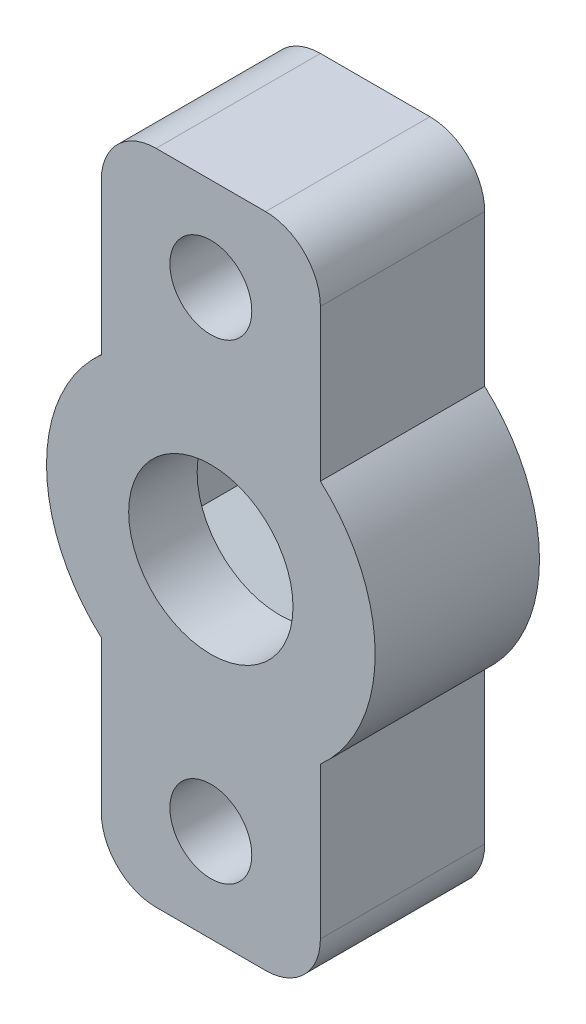
SolidWorks part; units mm, degrees
ref_plane "前视基准面" through (0, 0, 0) normal (0, 0, 1) x (1, 0, 0)
ref_plane "上视基准面" through (0, 0, 0) normal (0, 1, 0) x (1, 0, 0)
ref_plane "右视基准面" through (0, 0, 0) normal (1, 0, 0) x (0, 0, -1)
sketch "草图1" plane through (0, 0, 0) normal (0, 0, 1) x (1, 0, 0)
  line L0 (-5.08, 12.7) -> (-5.08, 5.6796)
  line L1 (-2.54, 15.24) -> (2.54, 15.24)
  line L2 (5.08, 12.7) -> (5.08, 5.6796)
  line L3 (0, 0) -> (0, 27.9989) construction
  line L4 (0, 0) -> (25.2898, 0) construction
  line L5 (5.08, -12.7) -> (5.08, -5.6796)
  line L6 (-2.54, -15.24) -> (2.54, -15.24)
  line L7 (-5.08, -12.7) -> (-5.08, -5.6796)
  arc A0 (-5.08, 5.6796) -> (-5.08, -5.6796) centre (0, 0) ccw
  arc A1 (5.08, 12.7) -> (2.54, 15.24) centre (2.54, 12.7) ccw
  arc A2 (-2.54, 15.24) -> (-5.08, 12.7) centre (-2.54, 12.7) ccw
  arc A3 (5.08, -12.7) -> (2.54, -15.24) centre (2.54, -12.7) cw
  arc A4 (-2.54, -15.24) -> (-5.08, -12.7) centre (-2.54, -12.7) cw
  arc A5 (5.08, -5.6796) -> (5.08, 5.6796) centre (0, 0) ccw
  dimension "D1" = 15.24
  dimension "D5" = 2.54
  dimension "D2" = 10.16
  dimension "D3" = 5.08
  dimension "D4" = 15.24
extrude "凸台-拉伸1" add sketch "草图1" along normal blind 7.62
sketch "草图2" plane through (0, 0, 0) normal (0, 0, -1) x (-1, 0, 0)
  line L1 (5.5562, 3.2079) -> (0, 6.4158)
  line L2 (0, 6.4158) -> (-5.5563, 3.2079)
  line L3 (-5.5563, 3.2079) -> (-5.5562, -3.2079)
  line L4 (-5.5562, -3.2079) -> (0, -6.4158)
  line L5 (0, -6.4158) -> (5.5563, -3.2079)
  line L6 (5.5563, -3.2079) -> (5.5562, 3.2079)
  circle A0 centre (0, 0) radius 5.5563 construction
extrude "切除-拉伸1" cut sketch "草图2" against normal blind 4.445
sketch "草图3" plane through (0, 0, 4.445) normal (0, 0, -1) x (-1, 0, 0)
  circle A0 centre (0, 0) radius 3.81
  dimension "D1" = 7.62
extrude "切除-拉伸2" cut sketch "草图3" against normal blind 6.096
ref_plane "基准面1" through (0, 0, 0) normal (0, 1, 0) x (1, 0, 0)
hole_wizard "#6 Clearance Hole1" positions "Sketch1" profile "Sketch2" hole size "#6" standard "ANSI Inch"
sketch "Sketch1" plane through (0, 0, 0) normal (0, 0, -1) x (-1, 0, 0)
  point P0 (0, 10.922)
  point P8 (0, -10.922)
  dimension "D1" = 10.922
  dimension "D2" = 10.922
sketch "Sketch2" plane through (0, 10.922, 0) normal (1, 0, 0) x (0, 1, 0)
  line L0 (0, 0) -> (0, 26.5408)
  line L1 (0, 26.5408) -> (1.8986, 25.4)
  line L2 (1.8986, 25.4) -> (1.8986, 0)
  line L5 (1.8986, 0) -> (0, 0)
  line L10 (0, 26.5408) -> (-1.8987, 25.4) construction
  line L11 (0, -6.35) -> (0, 107.95) construction
  dimension "Hole Dia." = 3.7973
  dimension "Hole Depth" = 25.4
  dimension "Drill Angle" = 118
